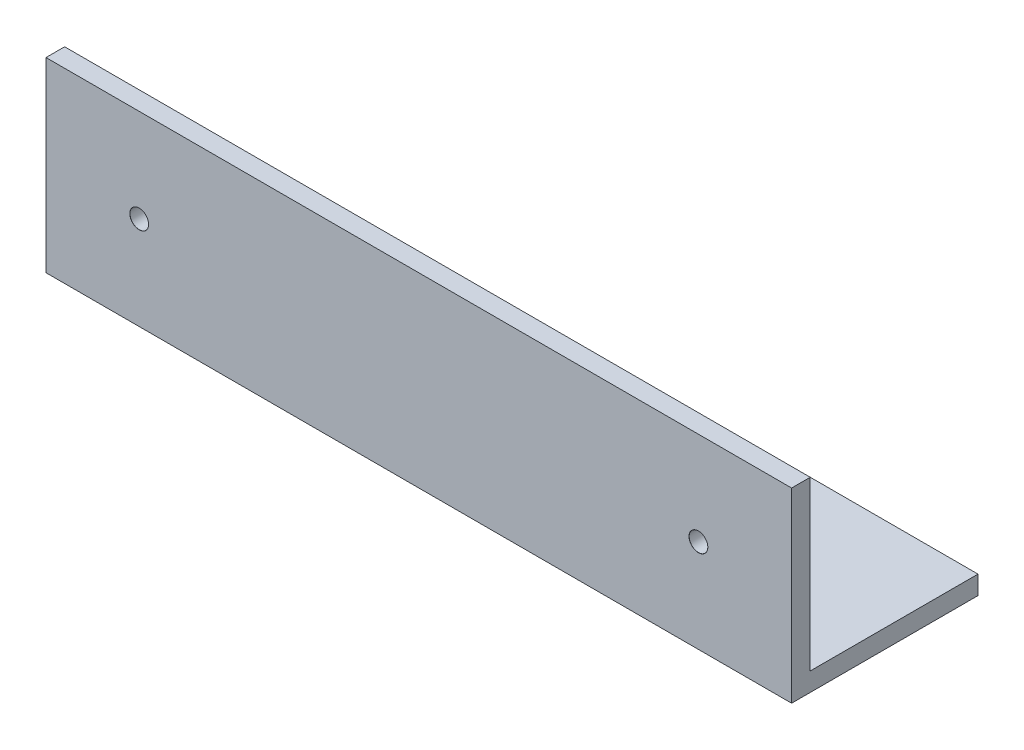
SolidWorks part; units mm, degrees
other "Connection Feature" parameters "D1"=200
ref_plane "Front Plane" through (0, 0, 0) normal (0, 0, 1) x (1, 0, 0)
ref_plane "Top Plane" through (0, 0, 0) normal (0, 1, 0) x (1, 0, 0)
ref_plane "Right Plane" through (0, 0, 0) normal (1, 0, 0) x (0, 0, -1)
sketch "Sketch2" plane through (0, 0, 0) normal (1, 0, 0) x (0, 0, -1)
  line L0 (0, 50) -> (0, 0)
  line L1 (0, 0) -> (50, 0)
extrude "Extrude-Thin1" add sketch "Sketch2" along normal mid plane 200 thin thin type one direction reverse wall 5
sketch "Sketch3" plane through (0, 0, -5) normal (0, 0, -1) x (-1, 0, 0)
  line L0 (0, 0) -> (0, 50) construction
  line L1 (-100, 50) -> (100, 50) construction
  line L2 (-75, 25) -> (75, 25) construction
  point P8 (0, 25)
  dimension "D1" = 150
hole_wizard "Ø5.0mm Dowel Hole1" positions "Sketch4" profile "Sketch5" hole size "Ø5.0" standard "ANSI Metric" end condition through all
sketch "Sketch4" plane through (0, 0, -5) normal (0, 0, -1) x (-1, 0, 0)
  point P0 (-75, 25)
  point P3 (75, 25)
sketch "Sketch5" plane through (75, 25, -5) normal (1, 0, 0) x (0, 1, 0)
  line L0 (0, 0) -> (0, 5)
  line L1 (0, 5) -> (2.525, 5)
  line L2 (2.5, 4.975) -> (2.5, 0)
  line L5 (2.5, 0) -> (0, 0)
  line L7 (2.525, 5) -> (2.5, 4.975)
  line L8 (-2.525, 5) -> (-2.5, 4.975) construction
  line L11 (0, -6.35) -> (0, 107.95) construction
  dimension "Thru Hole Dia." = 5
  dimension "Thru Hole Depth" = 5
  dimension "Far C'Sink Dia." = 5.05
  dimension "Far C'Sink Angle" = 90
hole_wizard "Ø5.0mm Dowel Hole2" positions "Sketch6" profile "Sketch7" hole size "Ø5.0" standard "ANSI Metric" end condition through all
sketch "Sketch6" plane through (0, 5, 0) normal (0, 1, 0) x (-1, 0, 0)
  line L0 (0, 0) -> (0, -50) construction
  line L1 (-100, -50) -> (100, -50) construction
  line L4 (-75, -25) -> (75, -25) construction
  line L8 (-75, -5) -> (75, -5) construction
  point P36 (-75, -25)
  point P38 (75, -25)
  point P44 (0, -25)
sketch "Sketch7" plane through (-75, 5, -25) normal (1, 0, 0) x (0, 0, 1)
  line L0 (0, 0) -> (0, 5)
  line L1 (0, 5) -> (2.525, 5)
  line L2 (2.5, 4.975) -> (2.5, 0)
  line L5 (2.5, 0) -> (0, 0)
  line L7 (2.525, 5) -> (2.5, 4.975)
  line L8 (-2.525, 5) -> (-2.5, 4.975) construction
  line L11 (0, -6.35) -> (0, 107.95) construction
  dimension "Thru Hole Dia." = 5
  dimension "Thru Hole Depth" = 5
  dimension "Far C'Sink Dia." = 5.05
  dimension "Far C'Sink Angle" = 90
other "Configuration Table"
